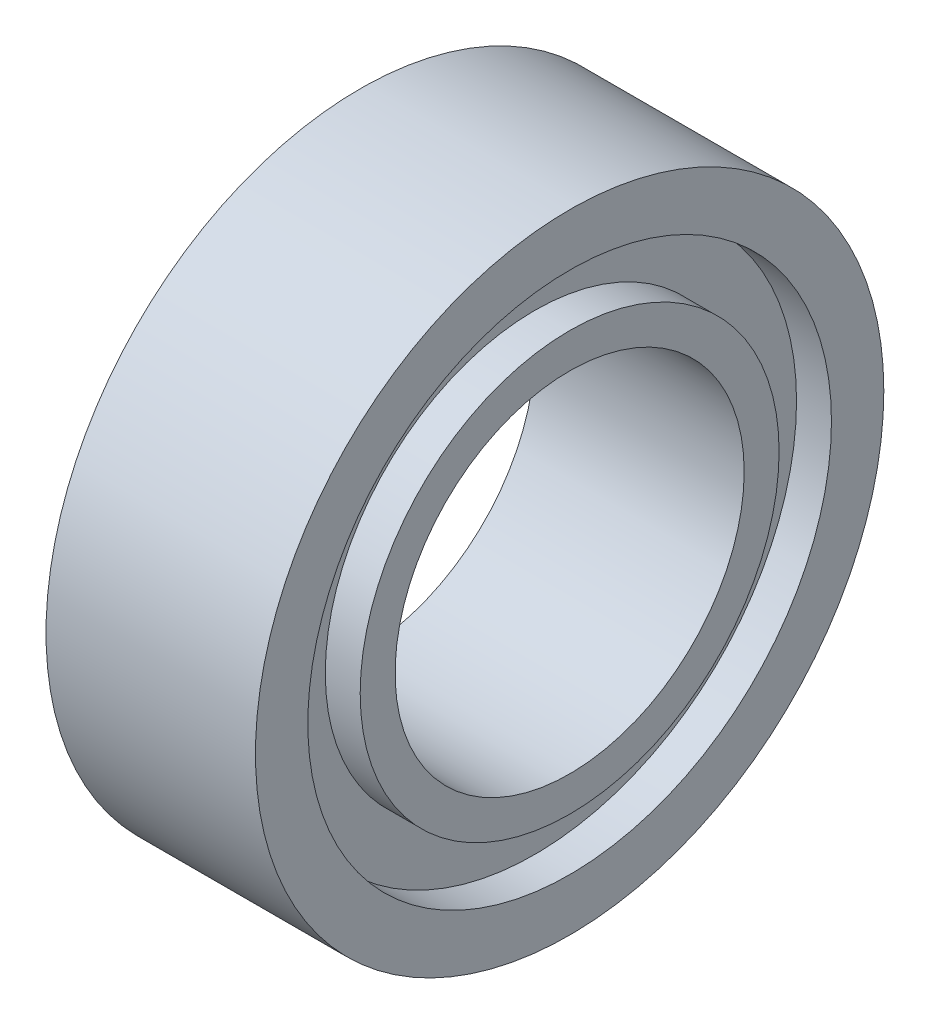
SolidWorks part; units mm, degrees
ref_plane "Front Plane" through (0, 0, 0) normal (0, 0, 1) x (1, 0, 0)
ref_plane "Top Plane" through (0, 0, 0) normal (0, 1, 0) x (1, 0, 0)
ref_plane "Right Plane" through (0, 0, 0) normal (1, 0, 0) x (0, 0, -1)
sketch "Sketch1" plane through (0, 0, 0) normal (1, 0, 0) x (0, 0, -1)
  circle A0 centre (0, 0) radius 4.5
  circle A1 centre (0, 0) radius 2.5
  dimension "D1" = 9
  dimension "D2" = 5
extrude "Boss-Extrude1" add sketch "Sketch1" along normal mid plane 3
sketch "Sketch2" plane through (1.5, 0, 0) normal (1, 0, 0) x (0, 0, -1)
  circle A0 centre (0, 0) radius 3
  circle A1 centre (0, 0) radius 3.75
  dimension "D1" = 6
  dimension "D2" = 7.5
extrude "Cut-Extrude1" cut sketch "Sketch2" against normal blind 0.5
